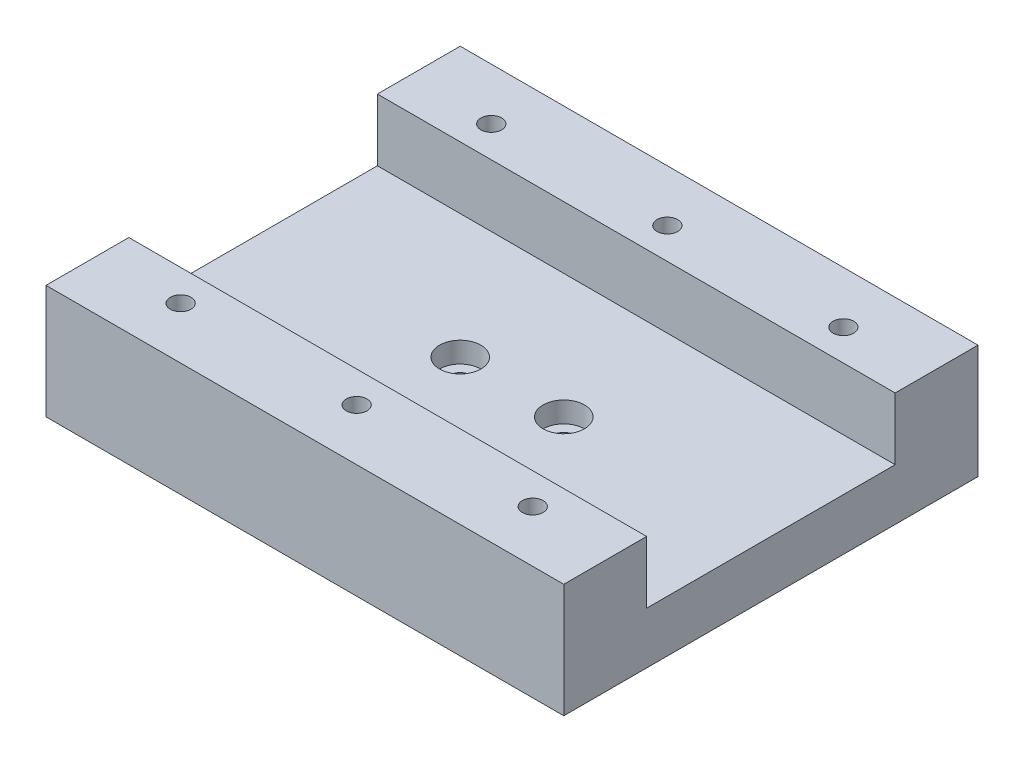
SolidWorks part; units mm, degrees
ref_plane "Front Plane" through (0, 0, 0) normal (0, 0, 1) x (1, 0, 0)
ref_plane "Top Plane" through (0, 0, 0) normal (0, 1, 0) x (1, 0, 0)
ref_plane "Right Plane" through (0, 0, 0) normal (1, 0, 0) x (0, 0, -1)
sketch "Sketch1" plane through (0, 0, 0) normal (0, 1, 0) x (1, 0, 0)
  line L1 (-25, 20) -> (25, 20)
  line L2 (-25, 20) -> (-25, -20)
  line L3 (-25, -20) -> (25, -20)
  line L4 (25, 20) -> (25, -20)
  line L5 (-25, 20) -> (25, -20) construction
  line L6 (-25, -20) -> (25, 20) construction
  point P0 (0, 0)
  dimension "D1" = 40
  dimension "D2" = 50
extrude "Boss-Extrude1" add sketch "Sketch1" along normal blind 5
sketch "Sketch2" plane through (0, 5, 0) normal (0, 1, 0) x (1, 0, 0)
  line L0 (-5, 0) -> (5, 0) construction
  circle A0 centre (-5, 0) radius 1
  circle A1 centre (5, 0) radius 1
  point P4 (0, 0)
  dimension "D2" = 2
  dimension "D3" = 2
  dimension "D1" = 10
extrude "Cut-Extrude1" cut sketch "Sketch2" against normal through all
sketch "Sketch3" plane through (0, 5, 0) normal (0, 1, 0) x (1, 0, 0)
  circle A0 centre (-5, 0) radius 2
  circle A1 centre (5, 0) radius 2
  dimension "D1" = 4
  dimension "D2" = 4
extrude "Cut-Extrude2" cut sketch "Sketch3" against normal blind 2
sketch "Sketch5" plane through (0, 5, 0) normal (0, 1, 0) x (1, 0, 0)
  line L0 (25, -20) -> (25, 20) construction
  line L1 (-25, 20) -> (25, 20)
  line L2 (-25, 20) -> (-25, 12)
  line L3 (-25, 12) -> (25, 12)
  line L4 (25, 20) -> (25, 12)
  line L6 (-25, -20) -> (25, -20)
  line L7 (-25, -20) -> (-25, -12)
  line L8 (-25, -12) -> (25, -12)
  line L9 (25, -20) -> (25, -12)
  dimension "D1" = 8
  dimension "D2" = 8
extrude "Boss-Extrude2" add sketch "Sketch5" along normal blind 6
sketch "Sketch4" plane through (0, 5, 0) normal (0, 1, 0) x (1, 0, 0)
  line L0 (0, 20) -> (0, -20) construction
  line L1 (25, 20) -> (-25, 20) construction
  line L2 (-25, -20) -> (25, -20) construction
  circle A0 centre (-17, 15) radius 1
  circle A1 centre (0, 15) radius 1
  circle A2 centre (17, 15) radius 1
  circle A3 centre (-17, -15) radius 1
  circle A4 centre (0, -15) radius 1
  circle A5 centre (17, -15) radius 1
  point P12 (0, 14.5633)
  point P19 (15.9019, 14.5633)
  point P20 (0, 0)
  point P22 (0, -15.8483)
  point P23 (0, 0)
  point P24 (0, 0)
  point P25 (0, 0)
  point P28 (14.0279, 17.7223)
  dimension "D1" = 2
  dimension "D2" = 2
  dimension "D3" = 2
  dimension "D4" = 2
  dimension "D5" = 2
  dimension "D6" = 2
  dimension "D7" = 15
  dimension "D8" = 15
  dimension "D9" = 17
  dimension "D10" = 17
  dimension "D11" = 17
  dimension "D12" = 17
extrude "Cut-Extrude3" cut sketch "Sketch4" against normal through all both and the other way through all
